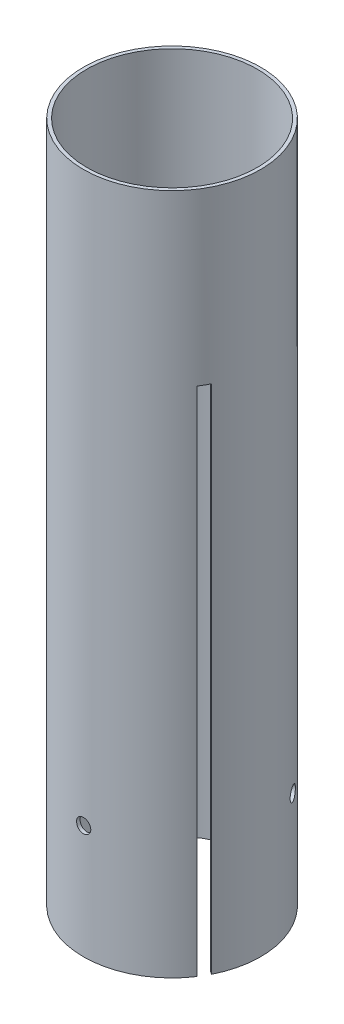
SolidWorks part; units mm, degrees
material "S-Glass Fiber"
ref_plane "Front Plane" through (0, 0, 0) normal (0, 0, 1) x (1, 0, 0)
ref_plane "Top Plane" through (0, 0, 0) normal (0, 1, 0) x (1, 0, 0)
ref_plane "Right Plane" through (0, 0, 0) normal (1, 0, 0) x (0, 0, -1)
sketch "Sketch2" plane through (0, 0, 0) normal (0, 1, 0) x (1, 0, 0)
  circle A0 centre (0, 0) radius 39.624
  circle A1 centre (0, 0) radius 38.1
  dimension "D1" = 79.248
  dimension "D2" = 76.2
extrude "Boss-Extrude1" add sketch "Sketch2" along normal blind 304.8 contours A1 | A0
sketch "Sketch3" plane through (0, 0, 0) normal (0, 0, 1) x (1, 0, 0)
  line L0 (-2.3812, 0) -> (2.3812, 0)
  line L1 (-39.624, 0) -> (39.624, 0) construction
  line L2 (2.3812, 0) -> (2.3812, 228.6)
  line L3 (2.3812, 228.6) -> (-2.3813, 228.6)
  line L4 (-2.3813, 228.6) -> (-2.3812, 0)
  point P6 (0, 0)
  dimension "D1" = 4.7625
  dimension "D2" = 228.6
extrude "Cut-Extrude1" cut sketch "Sketch3" against normal through all
pattern_circular "CirPattern1" count 3 over 360 about axis through (0, 0, 0) along (0, 1, 0) of "Cut-Extrude1"
sketch "Sketch4" plane through (0, 0, 0) normal (0, 0, 1) x (1, 0, 0)
  line L0 (-33.0627, 0) -> (33.0627, 0) construction
  circle A0 centre (0, 50.8) radius 3.175
  point P4 (0, 0)
  dimension "D1" = 6.35
  dimension "D2" = 50.8
extrude "Cut-Extrude3" cut sketch "Sketch4" along normal through all
pattern_circular "CirPattern2" count 3 over 360 about axis through (0, 304.8, 0) along (0, -1, 0) of "Cut-Extrude3"
